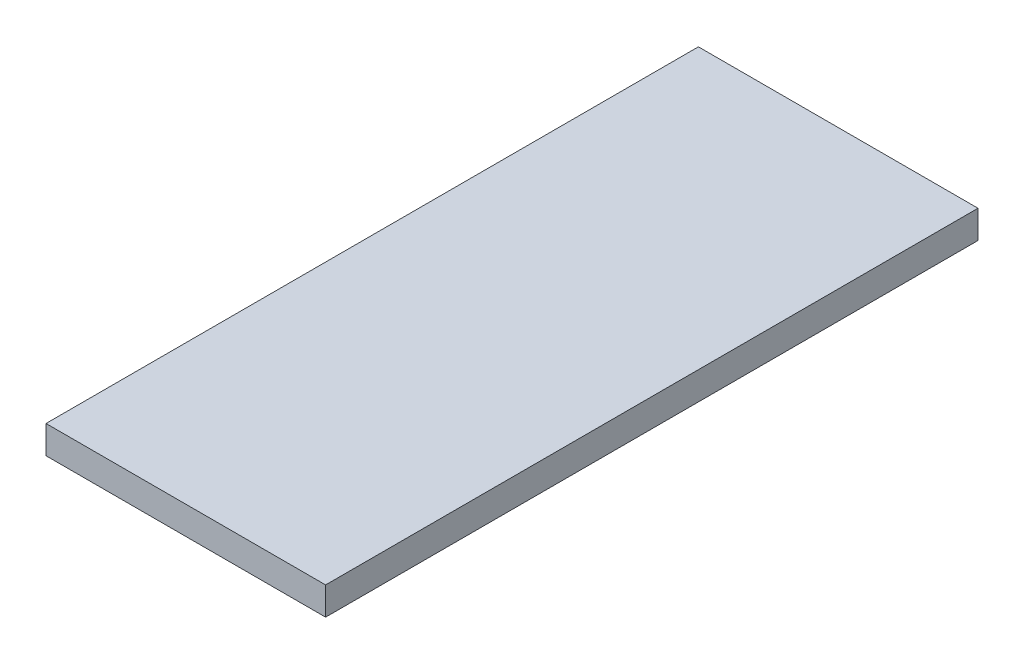
SolidWorks part; units mm, degrees
ref_plane "Спереди" through (0, 0, 0) normal (0, 0, 1) x (1, 0, 0)
ref_plane "Сверху" through (0, 0, 0) normal (0, 1, 0) x (1, 0, 0)
ref_plane "Справа" through (0, 0, 0) normal (1, 0, 0) x (0, 0, -1)
other "Configuration Table"
sketch "Эскиз1" plane through (0, 0, 0) normal (0, 1, 0) x (1, 0, 0)
  line L1 (15, -35) -> (-15, -35)
  line L2 (15, -35) -> (15, 35)
  line L3 (15, 35) -> (-15, 35)
  line L4 (-15, -35) -> (-15, 35)
  line L5 (15, -35) -> (-15, 35) construction
  line L6 (15, 35) -> (-15, -35) construction
  point P0 (0, 0)
  dimension "D1" = 30
  dimension "D2" = 70
extrude "Бобышка-Вытянуть1" add sketch "Эскиз1" along normal blind 3
